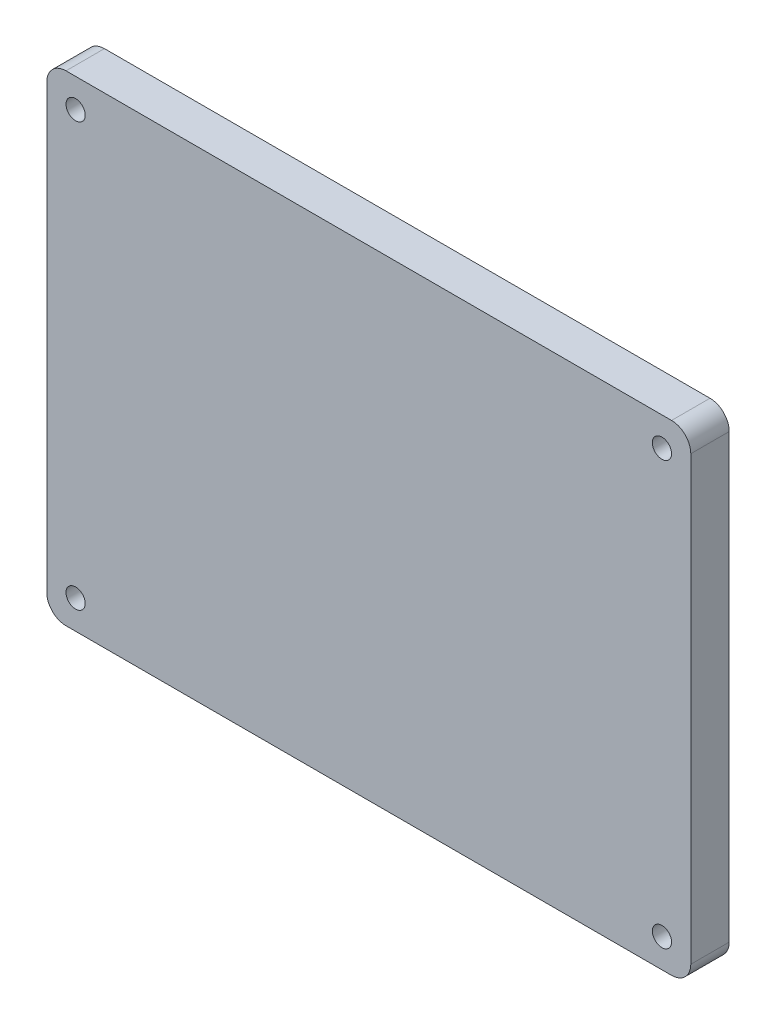
SolidWorks part; units mm, degrees
ref_plane "Plan de face" through (0, 0, 0) normal (0, 0, 1) x (1, 0, 0)
ref_plane "Plan de dessus" through (0, 0, 0) normal (0, 1, 0) x (1, 0, 0)
ref_plane "Plan de droite" through (0, 0, 0) normal (1, 0, 0) x (0, 0, -1)
sketch "Esquisse1" plane through (0, 0, 0) normal (0, 0, 1) x (1, 0, 0)
  line L1 (0, 0) -> (335, 0)
  line L2 (0, 0) -> (0, 250)
  line L3 (0, 250) -> (335, 250)
  line L4 (335, 0) -> (335, 250)
  dimension "D1" = 335
  dimension "D2" = 250
extrude "Boss.-Extru.1" add sketch "Esquisse1" along normal blind 20
sketch "Esquisse2" plane through (0, 0, 20) normal (0, 0, 1) x (1, 0, 0)
  line L0 (167.5, 0) -> (167.5, 125) construction
  line L1 (0, 0) -> (335, 0) construction
  line L2 (167.5, 125) -> (0, 125) construction
  line L3 (0, 250) -> (0, 0) construction
  circle A0 centre (15, 15) radius 5
  circle A1 centre (320, 15) radius 5
  circle A2 centre (320, 235) radius 5
  circle A3 centre (15, 235) radius 5
  dimension "D1" = 10
  dimension "D2" = 305
  dimension "D3" = 220
extrude "Enlèv. mat.-Extru.1" cut sketch "Esquisse2" against normal through all both and the other way through all
fillet "Congé1" radius 10 4 edges at (335, 250, 10) (335, 0, 10) (0, 0, 10) (0, 250, 10)
